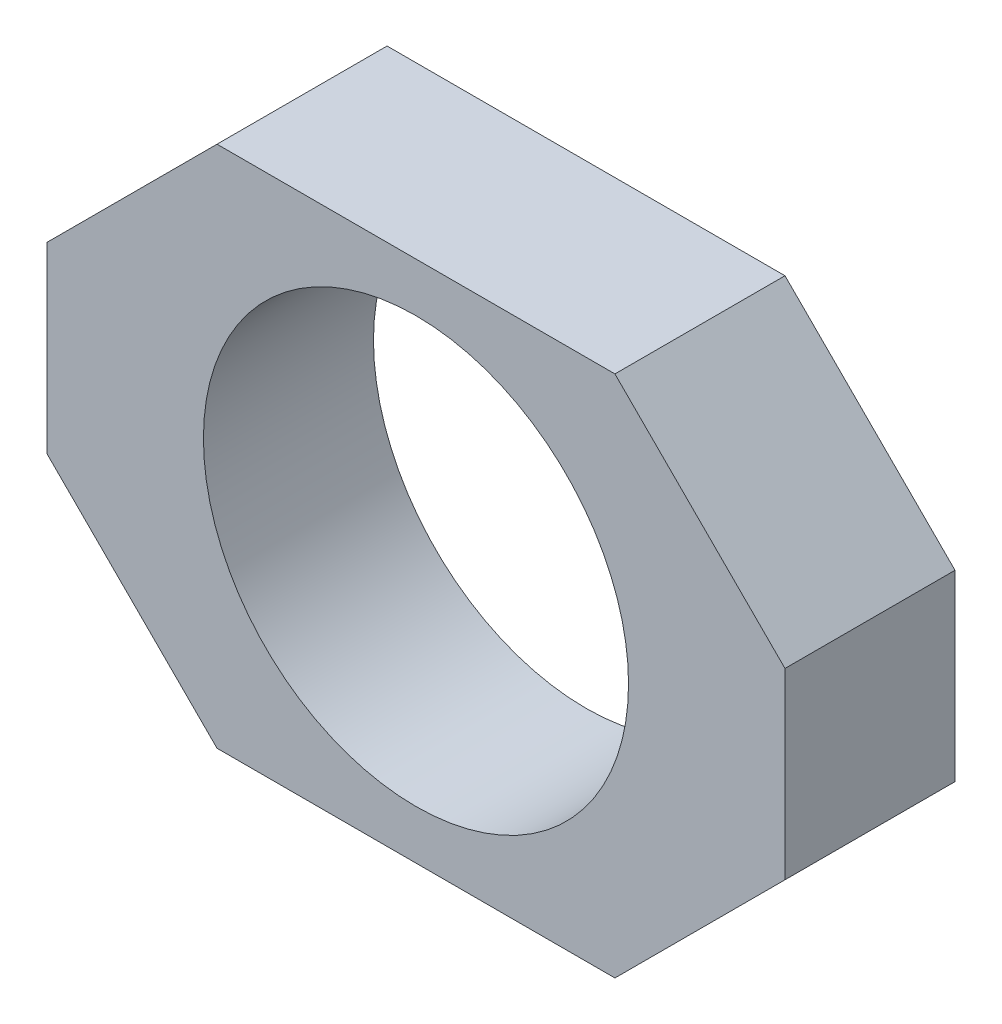
SolidWorks part; units mm, degrees
ref_plane "Front Plane" through (0, 0, 0) normal (0, 0, 1) x (1, 0, 0)
ref_plane "Top Plane" through (0, 0, 0) normal (0, 1, 0) x (1, 0, 0)
ref_plane "Right Plane" through (0, 0, 0) normal (1, 0, 0) x (0, 0, -1)
sketch "Sketch1" plane through (0, 0, 0) normal (0, 0, 1) x (1, 0, 0)
  line L1 (-55.1185, -39.0725) -> (55.1185, -39.0725)
  line L2 (-55.1185, -39.0725) -> (-55.1185, 39.0725)
  line L3 (-55.1185, 39.0725) -> (55.1185, 39.0725)
  line L4 (55.1185, -39.0725) -> (55.1185, 39.0725)
  line L5 (-55.1185, -39.0725) -> (55.1185, 39.0725) construction
  line L6 (-55.1185, 39.0725) -> (55.1185, -39.0725) construction
  point P0 (0, 0)
extrude "Boss-Extrude1" add sketch "Sketch1" against normal blind 25.4
sketch "Sketch2" plane through (0, 0, 0) normal (0, 0, 1) x (1, 0, 0)
  circle A0 centre (0, 0) radius 31.75
  dimension "D1" = 63.5
extrude "Cut-Extrude1" cut sketch "Sketch2" against normal through all
chamfer "Chamfer1" distance 25.4 angle 45 4 edges at (-55.1185, -39.0725, -12.7) (55.1185, -39.0725, -12.7) (-55.1185, 39.0725, -12.7) (55.1185, 39.0725, -12.7)
